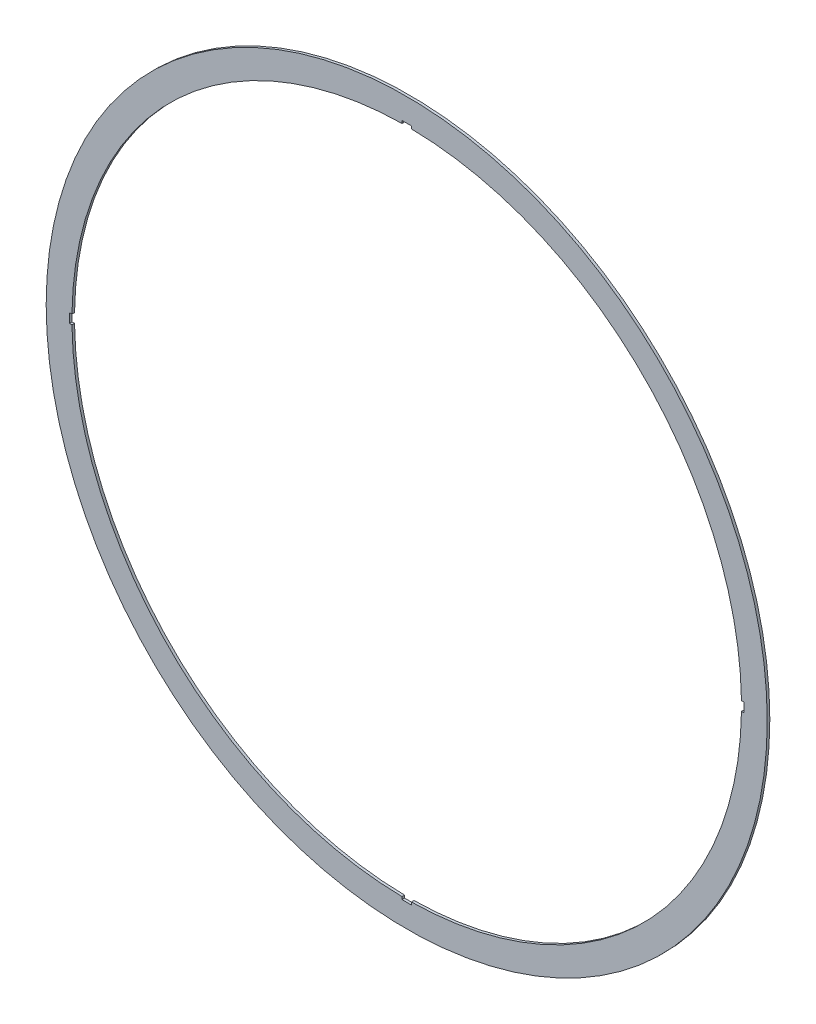
SolidWorks part; units mm, degrees
ref_plane "Front Plane" through (0, 0, 0) normal (0, 0, 1) x (1, 0, 0)
ref_plane "Top Plane" through (0, 0, 0) normal (0, 1, 0) x (1, 0, 0)
ref_plane "Right Plane" through (0, 0, 0) normal (1, 0, 0) x (0, 0, -1)
sketch "Sketch1" plane through (0, 0, 0) normal (0, 0, 1) x (1, 0, 0)
  line L0 (0, 0) -> (0, 484.7894) construction
  line L1 (393.0039, 5.4419) -> (389.962, 5.4419)
  line L2 (-5.4419, 393.0039) -> (5.4419, 393.0039)
  line L3 (-5.4419, 393.0039) -> (-5.4419, 389.962)
  line L5 (5.4419, 393.0039) -> (5.4419, 389.962)
  line L6 (-5.4419, 393.0039) -> (0, 390) construction
  line L7 (0, 390) -> (5.4419, 393.0039) construction
  line L8 (393.0039, 5.4419) -> (393.0039, -5.4419)
  line L9 (393.0039, -5.4419) -> (389.962, -5.4419)
  line L10 (5.4419, -393.0039) -> (5.4419, -389.962)
  line L11 (5.4419, -393.0039) -> (-5.4419, -393.0039)
  line L12 (-5.4419, -393.0039) -> (-5.4419, -389.962)
  line L13 (-393.0039, -5.4419) -> (-389.962, -5.4419)
  line L14 (-393.0039, -5.4419) -> (-393.0039, 5.4419)
  line L15 (-393.0039, 5.4419) -> (-389.962, 5.4419)
  circle A0 centre (0, 0) radius 420
  arc A1 (-5.4419, 389.962) -> (-389.962, 5.4419) centre (0, 0) ccw
  arc A2 (389.962, 5.4419) -> (5.4419, 389.962) centre (0, 0) ccw
  circle A3 centre (0, 0) radius 390 construction
  arc A4 (5.4419, -389.962) -> (389.962, -5.4419) centre (0, 0) ccw
  arc A5 (-389.962, -5.4419) -> (-5.4419, -389.962) centre (0, 0) ccw
  point P5 (0, 390)
  point P7 (430, 0)
  dimension "D1" = 30
  dimension "D3" = 840
  dimension "D2" = 4
extrude "Boss-Extrude1" add sketch "Sketch1" along normal blind 3
